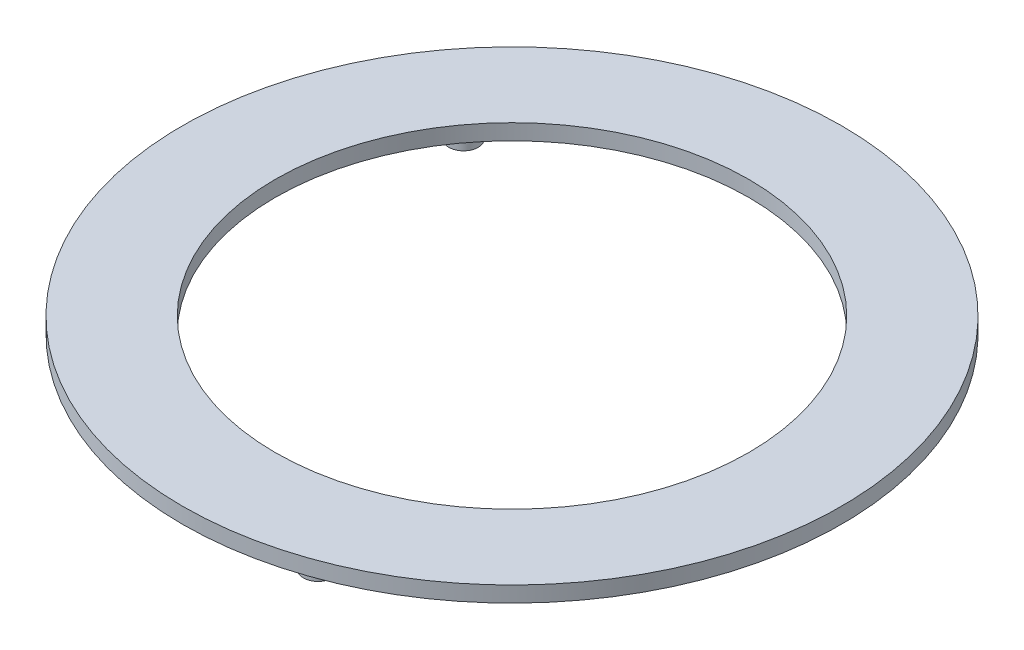
SolidWorks part; units mm, degrees
ref_plane "Front Plane" through (0, 0, 0) normal (0, 0, 1) x (1, 0, 0)
ref_plane "Top Plane" through (0, 0, 0) normal (0, 1, 0) x (1, 0, 0)
ref_plane "Right Plane" through (0, 0, 0) normal (1, 0, 0) x (0, 0, -1)
sketch "Sketch1" plane through (0, 0, 0) normal (0, 1, 0) x (1, 0, 0)
  line L0 (0, -41.439) -> (0, 59.5224) construction
  line L1 (-42.487, -10.5704) -> (53.5331, 20.6284) construction
  line L2 (-26.2584, 39.3761) -> (33.0853, -42.3035) construction
  line L3 (26.2584, 39.3761) -> (-33.0853, -42.3035) construction
  line L4 (42.487, -10.5704) -> (-53.5331, 20.6284) construction
  line L5 (0, 3.2345) -> (0, -41.439) construction
  circle A0 centre (0, 0) radius 31.5
  circle A1 centre (0, 0) radius 22.625
  point P4 (0, 24.1)
  dimension "D1" = 63
  dimension "D2" = 45.25
  dimension "D3" = 24.1
  dimension "D4" = 5
  dimension "D5" = 44.6735
extrude "Boss-Extrude1" add sketch "Sketch1" along normal blind 1.5
sketch "Sketch2" plane through (0, 0, 0) normal (0, 1, 0) x (1, 0, 0)
  line L0 (0, 0) -> (-21.2646, 16.6378) construction
  circle A0 centre (-21.2646, 16.6378) radius 1.4
  circle A1 centre (0, 0) radius 22.625 construction
  circle A2 centre (9.2523, 25.3652) radius 1.4
  circle A3 centre (26.9829, -0.9612) radius 1.4
  circle A4 centre (7.424, -25.9593) radius 1.4
  circle A5 centre (-22.3946, -15.0825) radius 1.4
  point P0 (-21.2646, 16.6378)
  dimension "D1" = 2.8
  dimension "D2" = 27
  dimension "D4" = 27
  dimension "D3" = 5
extrude "Boss-Extrude2" add sketch "Sketch2" against normal blind 2.8
